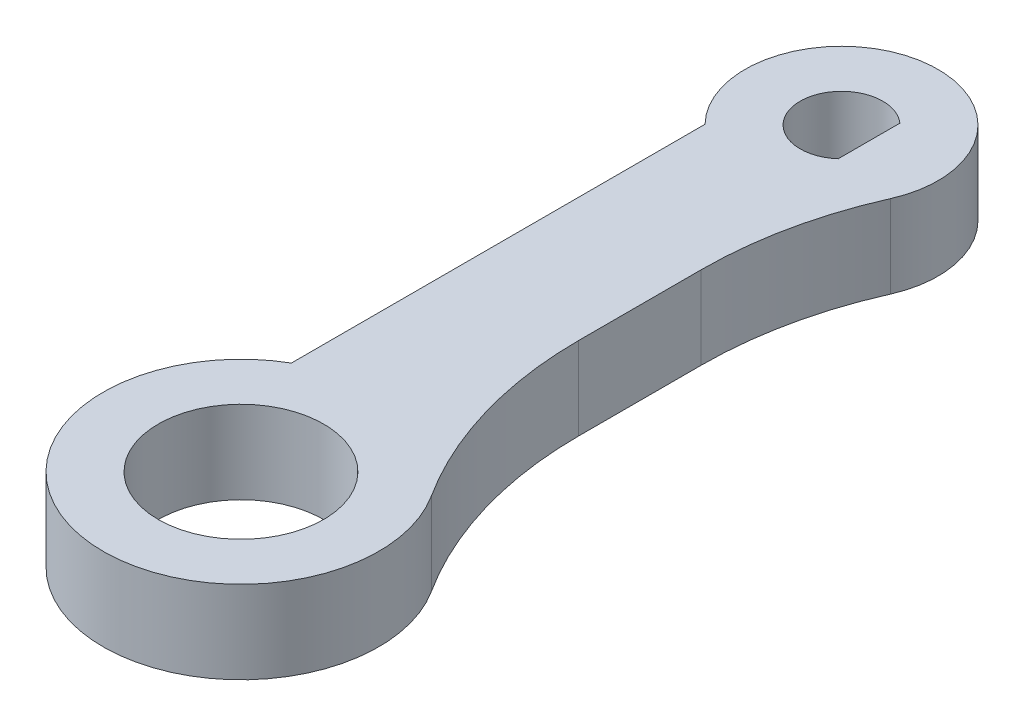
SolidWorks part; units mm, degrees
ref_plane "前视基准面" through (0, 0, 0) normal (0, 0, 1) x (1, 0, 0)
ref_plane "上视基准面" through (0, 0, 0) normal (0, 1, 0) x (1, 0, 0)
ref_plane "右视基准面" through (0, 0, 0) normal (1, 0, 0) x (0, 0, -1)
other "Configuration Table"
sketch "草图2" plane through (0, 0, 0) normal (0, 1, 0) x (1, 0, 0)
  line L14 (1, 1.118) -> (1, -1.118)
  line L15 (-2.5, -2.4495) -> (2.5, -2.4495)
  line L16 (-2.5, -2.4495) -> (-2.5, -17.4495)
  line L17 (-2.5, -17.4495) -> (2.5, -17.4495)
  line L18 (2.5, -2.4495) -> (2.5, -17.4495)
  circle A14 centre (0, 0) radius 3.5
  circle A15 centre (0, 0) radius 1.5
  circle A16 centre (0, -21.7796) radius 3
  circle A17 centre (0, -21.7796) radius 5
  dimension "D1" = 3
  dimension "D2" = 2
  dimension "D6" = 6
  dimension "D7" = 2
  dimension "D3" = 5
  dimension "D4" = 15
  dimension "D5" = 1
extrude "凸台-拉伸1" add sketch "草图2" along normal blind 3 contours L15 A14 A15 | L17 A17 A16 | L14 A15
sketch "草图3" plane through (0, 0, 0) normal (0, -1, 0) x (1, 0, 0)
  line L0 (2, 17.197) -> (2, 2.8723)
  line L1 (-2.5, 2.4495) -> (-2.5, 17.4495) construction
  circle A0 centre (0, 21.7796) radius 5
  circle A1 centre (0, 0) radius 3.5
  arc A2 (2.5, 17.4495) -> (-2.5, 17.4495) centre (0, 21.7796) ccw construction
  arc A3 (-2.5, 2.4495) -> (2.5, 2.4495) centre (0, 0) ccw construction
  line M7 (2.5, 2.4495) -> (2.5, 17.4495)
  dimension "D1" = 2
extrude "切除-拉伸1" cut sketch "草图3" against normal through all contours A1 A0 L0 M7
fillet "圆角1" radius 14 2 edges at (2, 1.5, 2.8723) (2, 1.5, 17.197)
